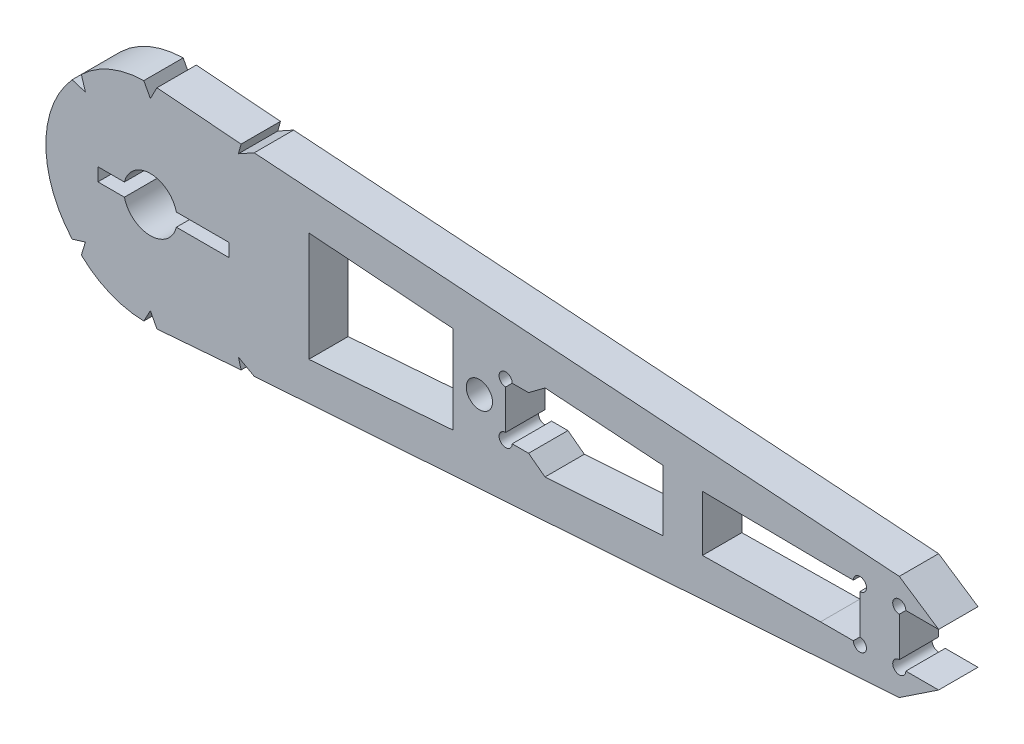
SolidWorks part; units mm, degrees
ref_plane "前视基准面" through (0, 0, 0) normal (0, 0, 1) x (1, 0, 0)
ref_plane "上视基准面" through (0, 0, 0) normal (0, 1, 0) x (1, 0, 0)
ref_plane "右视基准面" through (0, 0, 0) normal (1, 0, 0) x (0, 0, -1)
sketch "草图1" plane through (0, 0, 0) normal (0, 0, 1) x (1, 0, 0)
  line L0 (42.0739, 2.1168) -> (51.0739, 2)
  line L1 (51.0739, 2) -> (53.5739, 2)
  line L2 (42.0739, -2.1168) -> (51.0739, -2)
  line L3 (51.0739, -2) -> (53.5739, -2)
  line L4 (60.0739, -2) -> (57.0739, -4)
  line L5 (57.0739, -4) -> (7.9138, -7.376)
  line L6 (7.9138, 7.376) -> (57.0739, 4)
  line L7 (57.0739, 4) -> (60.0739, 2)
  line L8 (42.0739, 2.1168) -> (42.0739, -2.1168)
  line L9 (54.0739, 1.5) -> (54.0739, -1.5)
  line L10 (27.5739, 2) -> (28.8239, 2)
  line L11 (27.0739, -1.5) -> (27.0739, 1.5)
  line L12 (27.5739, -2) -> (28.8239, -2)
  line L13 (28.8239, -2) -> (30.0739, -2.9391)
  line L14 (30.0739, -2.9391) -> (39.0739, -2.3223)
  line L15 (39.0739, 2.3223) -> (39.0739, -2.3223)
  line L16 (30.0739, 2.9391) -> (39.0739, 2.3223)
  line L17 (30.0739, 2.9391) -> (28.8239, 2)
  line L18 (-4, 0.5) -> (-1.9803, 0.5)
  line L19 (-4, 0.5) -> (-4, -0.5)
  line L20 (-4, -0.5) -> (-1.9803, -0.5)
  line L21 (1.9803, -0.5) -> (6, -0.5)
  line L22 (6, 0.5) -> (6, -0.5)
  line L23 (1.9803, 0.5) -> (6, 0.5)
  line L24 (12.0739, -4.1726) -> (23.0739, -3.3503)
  line L25 (23.0739, 3.3503) -> (23.0739, -3.3503)
  line L26 (12.0739, 4.1726) -> (23.0739, 3.3503)
  line L27 (12.0739, 4.1726) -> (12.0739, -4.1726)
  line L28 (7.9138, -7.376) -> (6.7082, -6.7082)
  line L29 (6.9169, -7.4546) -> (6.7082, -6.7082)
  line L30 (0.5, -7.9606) -> (6.9169, -7.4546)
  line L31 (0, -7) -> (0.5, -7.9606)
  line L32 (-0.5, -7.9342) -> (0, -7)
  line L33 (-4.9497, -4.9497) -> (-5.2602, -5.9612)
  line L34 (-5.9612, -5.2602) -> (-4.9497, -4.9497)
  line L35 (-5.9612, 5.2602) -> (-4.9497, 4.9497)
  line L36 (-5.2602, 5.9612) -> (-4.9497, 4.9497)
  line L37 (0, 7) -> (-0.5, 7.9342)
  line L38 (0, 7) -> (0.5, 7.9606)
  line L39 (0.5, 7.9606) -> (6.9169, 7.4546)
  line L40 (6.9169, 7.4546) -> (6.7082, 6.7082)
  line L41 (57.0739, -1.5) -> (57.0739, 1.5)
  line L42 (57.5739, -2) -> (60.0739, -2)
  line L43 (6.7082, 6.7082) -> (7.9138, 7.376)
  line L44 (60.0739, 2) -> (57.5739, 2)
  circle A0 centre (25.0739, 0) radius 1
  arc A1 (53.5739, -2) -> (54.0739, -1.5) centre (54.0739, -2) ccw
  arc A2 (54.0739, 1.5) -> (53.5739, 2) centre (54.0739, 2) ccw
  arc A3 (27.5739, 2) -> (27.0739, 1.5) centre (27.0739, 2) ccw
  arc A4 (27.0739, -1.5) -> (27.5739, -2) centre (27.0739, -2) ccw
  arc A5 (-1.9803, -0.5) -> (1.9803, -0.5) centre (0, -0.013) ccw
  arc A6 (1.9803, 0.5) -> (-1.9803, 0.5) centre (0, 0.013) ccw
  arc A7 (-5.2602, -5.9612) -> (-0.5, -7.9342) centre (-0.3719, -0.896) ccw
  arc A8 (-5.9612, 5.2602) -> (-5.9612, -5.2602) centre (-0.0649, 0) ccw
  arc A9 (-0.5, 7.9342) -> (-5.2602, 5.9612) centre (-0.3719, 0.896) ccw
  arc A10 (57.0739, -1.5) -> (57.5739, -2) centre (57.0739, -2) ccw
  arc A11 (57.5739, 2) -> (57.0739, 1.5) centre (57.0739, 2) ccw
extrude "凸台-拉伸1" add sketch "草图1" along normal blind 3
